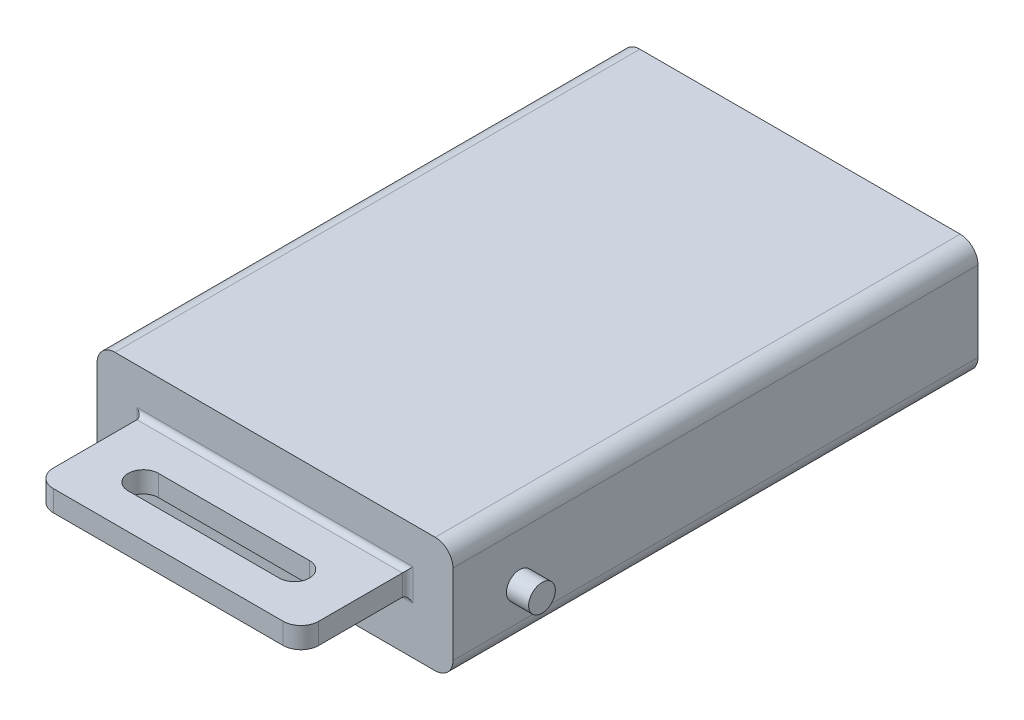
SolidWorks part; units mm, degrees
ref_plane "Front Plane" through (0, 0, 0) normal (0, 0, 1) x (1, 0, 0)
ref_plane "Top Plane" through (0, 0, 0) normal (0, 1, 0) x (1, 0, 0)
ref_plane "Right Plane" through (0, 0, 0) normal (1, 0, 0) x (0, 0, -1)
sketch "Sketch1" plane through (0, 0, 0) normal (0, 0, 1) x (1, 0, 0)
  line L1 (2.54, 0) -> (48.26, 0)
  line L2 (0, 2.54) -> (0, 13.97)
  line L3 (2.54, 16.51) -> (48.26, 16.51)
  line L4 (50.8, 2.54) -> (50.8, 13.97)
  arc A0 (2.54, 16.51) -> (0, 13.97) centre (2.54, 13.97) ccw
  arc A1 (50.8, 13.97) -> (48.26, 16.51) centre (48.26, 13.97) ccw
  arc A2 (50.8, 2.54) -> (48.26, 0) centre (48.26, 2.54) cw
  arc A3 (0, 2.54) -> (2.54, 0) centre (2.54, 2.54) ccw
  point P7 (0, 16.51)
  point P10 (50.8, 16.51)
  point P13 (50.8, 0)
  point P16 (0, 0)
  dimension "D3" = 2.54
  dimension "D1" = 50.8
  dimension "D2" = 16.51
extrude "Extrude1" add sketch "Sketch1" against normal blind 74.93
sketch "Sketch2" plane through (0, 0, 0) normal (1, 0, 0) x (0, 0, -1)
  line L0 (0, 16.51) -> (81.9553, 16.51) construction
  circle A0 centre (9.525, 7.112) radius 1.905
  dimension "D1" = 3.81
  dimension "D2" = 9.525
  dimension "D3" = 7.112
extrude "Extrude2" add sketch "Sketch2" against normal blind 3.175
ref_plane "Plane1" through (25.4, 0, 0) normal (1, 0, 0) x (0, 0, -1)
mirror "Mirror1" about plane through (25.4, 0, 0) normal (1, 0, 0) of "Extrude2"
sketch "Sketch3" plane through (0, 0, 0) normal (0, 0, 1) x (1, 0, 0)
  line L0 (0, 9.017) -> (50.8, 9.017) construction
  line L2 (6.4598, 10.5173) -> (44.3402, 10.5173)
  line L3 (6.4598, 10.5173) -> (6.4598, 7.5167)
  line L4 (6.4598, 7.5167) -> (44.3402, 7.5167)
  line L5 (44.3402, 10.5173) -> (44.3402, 7.5167)
  point P4 (25.4, 9.017)
extrude "Extrude3" add sketch "Sketch3" along normal blind 15.24
fillet "Fillet1" radius 2.54 2 edges at (6.4598, 9.017, 15.24) (44.3402, 9.017, 15.24)
fillet "Fillet2" radius 0.762 4 edges at (6.4598, 9.017, 0) (25.4, 7.5167, 0) (44.3402, 9.017, 0) (25.4, 10.5173, 0)
ref_plane "Plane2" through (0, 10.5173, 0) normal (0, 1, 0) x (-1, 0, 0)
sketch "Sketch4" plane through (0, 10.5173, 0) normal (0, 1, 0) x (-1, 0, 0)
  line L0 (-36.1792, 8.0202) -> (-14.6208, 8.0202) construction
  line L1 (-36.1792, 10.1837) -> (-14.6208, 10.1837)
  line L2 (-36.1792, 5.8567) -> (-14.6208, 5.8567)
  arc A0 (-36.1792, 10.1837) -> (-36.1792, 5.8567) centre (-36.1792, 8.0202) ccw
  arc A1 (-14.6208, 5.8567) -> (-14.6208, 10.1837) centre (-14.6208, 8.0202) ccw
  point P2 (-25.4, 8.0202)
  dimension "D1" = 4.327
  dimension "D2" = 21.5585
extrude "Extrude4" cut sketch "Sketch4" against normal blind 17.78
ref_plane "Plane3" through (0, 0, -74.93) normal (0, 0, -1) x (-1, 0, 0)
sketch "Sketch5" plane through (0, 0, -74.93) normal (0, 0, -1) x (-1, 0, 0)
  line L0 (-50.8, 8.255) -> (0, 8.255) construction
  line L1 (-50.8, 2.54) -> (-50.8, 13.97) construction
  line L2 (0, 13.97) -> (0, 2.54) construction
  line L4 (-45.1921, 10.0156) -> (-5.6079, 10.0156)
  line L5 (-45.1921, 10.0156) -> (-45.1921, 6.4944)
  line L6 (-45.1921, 6.4944) -> (-5.6079, 6.4944)
  line L7 (-5.6079, 10.0156) -> (-5.6079, 6.4944)
  line L8 (-45.1921, 10.0156) -> (-5.6079, 6.4944) construction
  line L9 (-45.1921, 6.4944) -> (-5.6079, 10.0156) construction
  point P6 (-25.4, 8.255)
extrude "Extrude5" cut sketch "Sketch5" against normal blind 17.78
